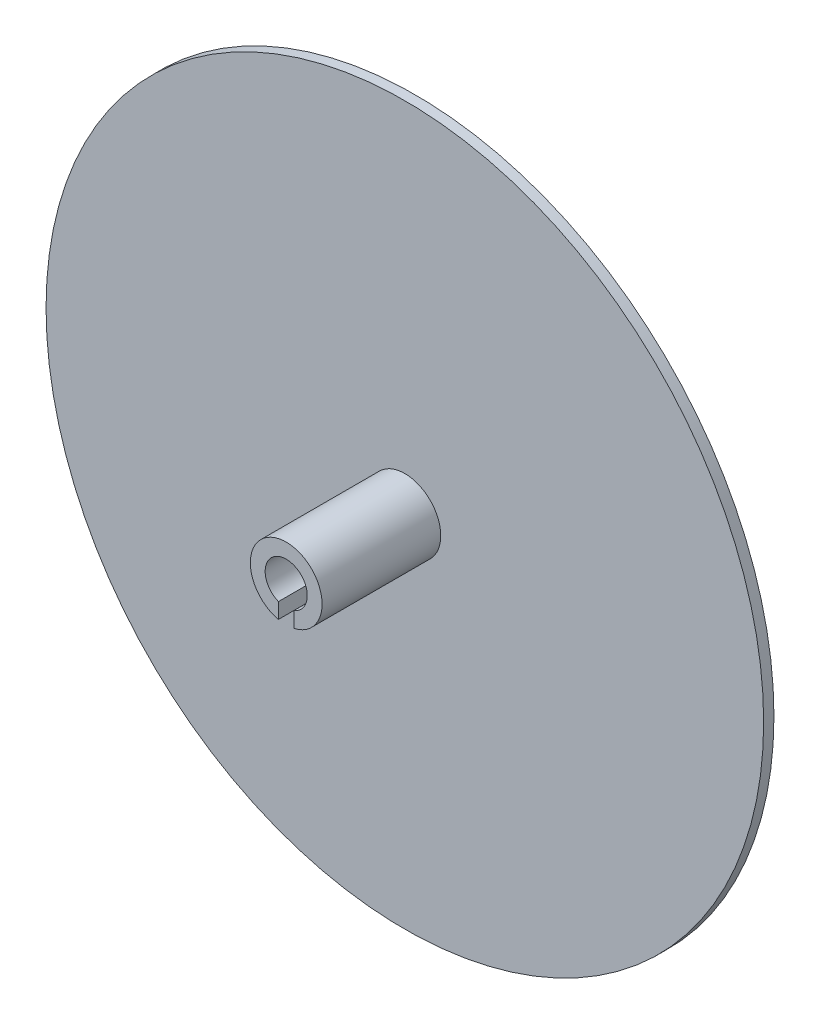
SolidWorks part; units mm, degrees
material "Lega 1060"
ref_plane "Piano frontale" through (0, 0, 0) normal (0, 0, 1) x (1, 0, 0)
ref_plane "Piano superiore" through (0, 0, 0) normal (0, 1, 0) x (1, 0, 0)
ref_plane "Piano destro" through (0, 0, 0) normal (1, 0, 0) x (0, 0, -1)
sketch "Schizzo1" plane through (0, 0, 0) normal (0, 0, 1) x (1, 0, 0)
  circle A0 centre (0, 0) radius 150
  dimension "D1" = 300
extrude "Estrusione-Estrusione1" add sketch "Schizzo1" along normal blind 4.3
sketch "Schizzo2" plane through (0, 0, 4.3) normal (0, 0, 1) x (1, 0, 0)
  circle A0 centre (0, 0) radius 15
  circle A1 centre (0, 0) radius 8.8
  dimension "D1" = 30
  dimension "D2" = 17.6
extrude "Estrusione-Estrusione2" add sketch "Schizzo2" along normal blind 49.6
sketch "Schizzo3" plane through (0, 0, 53.9) normal (0, 0, 1) x (1, 0, 0)
  line L0 (0, 0) -> (0, -15)
  line L2 (-3.25, -25) -> (3.25, -25)
  line L3 (-3.25, -25) -> (-3.25, -5)
  line L4 (-3.25, -5) -> (3.25, -5)
  line L5 (3.25, -25) -> (3.25, -5)
  line L6 (-3.25, -25) -> (3.25, -5) construction
  line L7 (-3.25, -5) -> (3.25, -25) construction
  circle A0 centre (0, 0) radius 15 construction
  circle M5 centre (0, 0) radius 15
  circle M6 centre (0, 0) radius 8.8
  dimension "D1" = 6.5
  dimension "D2" = 20
extrude "Taglio-Estrusione1" cut sketch "Schizzo3" against normal blind 17.25 contours L3 L0 M5 M6 | L5 L0 M5 M6
